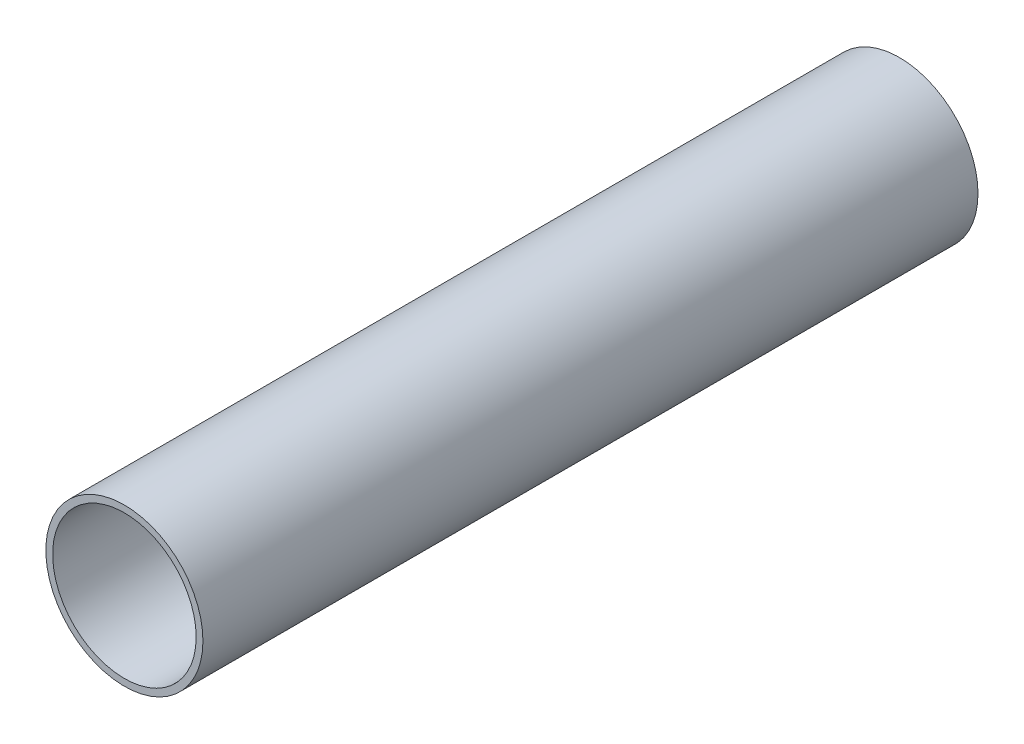
SolidWorks part; units mm, degrees
ref_plane "Front Plane" through (0, 0, 0) normal (0, 0, 1) x (1, 0, 0)
ref_plane "Top Plane" through (0, 0, 0) normal (0, 1, 0) x (1, 0, 0)
ref_plane "Right Plane" through (0, 0, 0) normal (1, 0, 0) x (0, 0, -1)
sketch "Sketch1" plane through (0, 0, 0) normal (0, 0, 1) x (1, 0, 0)
  circle A0 centre (0, 0) radius 17.375
  circle A1 centre (0, 0) radius 15.875
  dimension "D1" = 34.75
  dimension "D2" = 31.75
extrude "Boss-Extrude1" add sketch "Sketch1" along normal mid plane 171.45
